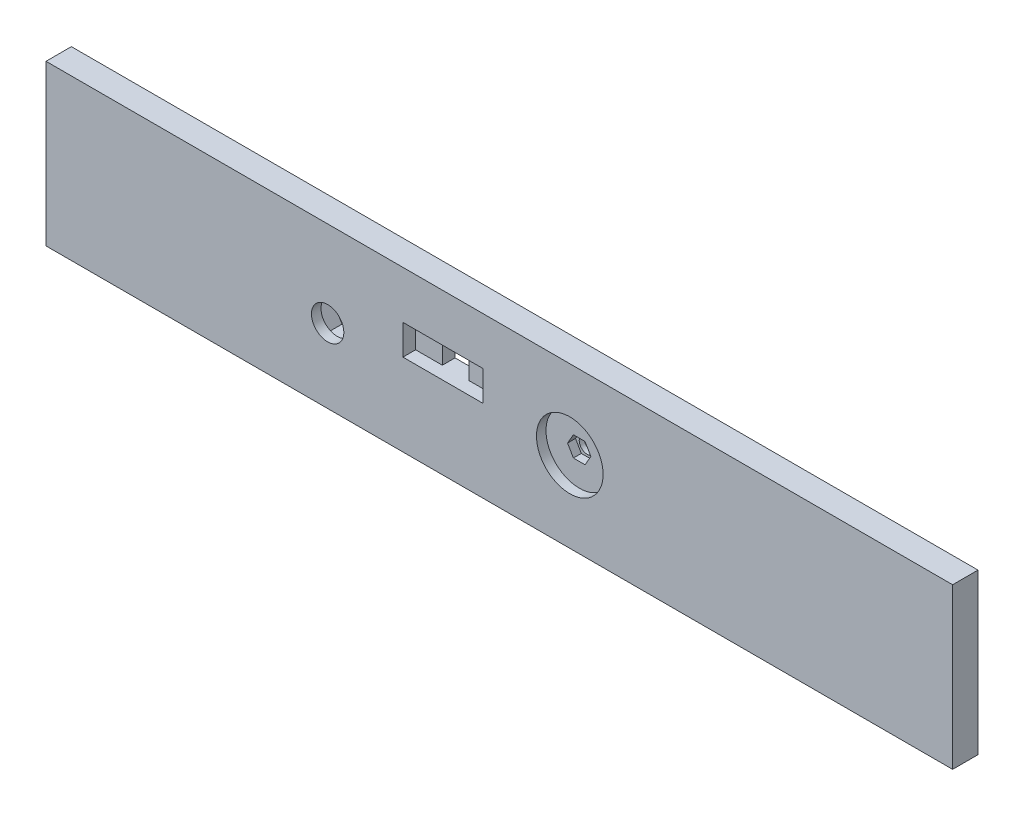
SolidWorks part; units mm, degrees
ref_plane "Front Plane" through (0, 0, 0) normal (0, 0, 1) x (1, 0, 0)
ref_plane "Top Plane" through (0, 0, 0) normal (0, 1, 0) x (1, 0, 0)
ref_plane "Right Plane" through (0, 0, 0) normal (1, 0, 0) x (0, 0, -1)
sketch "Sketch1" plane through (0, 0, 0) normal (0, 0, 1) x (1, 0, 0)
  line L1 (0, 0) -> (571.5, 0)
  line L2 (0, 0) -> (0, 100.8)
  line L3 (0, 100.8) -> (571.5, 100.8)
  line L4 (571.5, 0) -> (571.5, 100.8)
  dimension "D1" = 100.8
  dimension "D2" = 571.5
extrude "Boss-Extrude1" add sketch "Sketch1" along normal mid plane 16
sketch "Sketch4" plane through (0, 0, -8) normal (0, 0, -1) x (-1, 0, 0)
  line L3 (-571.5, 100.8) -> (0, 100.8) construction
  circle A0 centre (-330.1236, 50.8) radius 7.5
  dimension "D3" = 15
  dimension "D1" = 50
extrude "Cut-Extrude3" cut sketch "Sketch4" against normal blind 2
sketch "Sketch5" plane through (0, 0, -6) normal (0, 0, -1) x (-1, 0, 0)
  circle A0 centre (-330.1236, 50.8) radius 5
  dimension "D1" = 10
extrude "Cut-Extrude4" cut sketch "Sketch5" against normal through all
sketch "Sketch6" plane through (0, 0, 8) normal (0, 0, 1) x (1, 0, 0)
  line L1 (337.4675, 50.8) -> (333.7956, 57.16)
  line L2 (333.7956, 57.16) -> (326.4517, 57.16)
  line L3 (326.4517, 57.16) -> (322.7797, 50.8)
  line L4 (322.7797, 50.8) -> (326.4517, 44.44)
  line L5 (326.4517, 44.44) -> (333.7956, 44.44)
  line L6 (333.7956, 44.44) -> (337.4675, 50.8)
  circle A0 centre (330.1236, 50.8) radius 6.36 construction
  dimension "D1" = 12.72
extrude "Cut-Extrude5" cut sketch "Sketch6" against normal blind 11
sketch "Sketch9" plane through (0, 0, 8) normal (0, 0, 1) x (1, 0, 0)
  circle A0 centre (177.5367, 46.6) radius 10.2
  dimension "D1" = 20.4
extrude "power and usb cables" cut sketch "Sketch9" against normal through all
sketch "Sketch10" plane through (0, 0, 8) normal (0, 0, 1) x (1, 0, 0)
  circle A0 centre (330.1639, 50.8218) radius 21
extrude "Cut-Extrude6" cut sketch "Sketch10" against normal blind 6
sketch "Sketch12" plane through (0, 0, -8) normal (0, 0, -1) x (-1, 0, 0)
  line L0 (-164.3354, 47.7347) -> (-169.9534, 57.4654) construction
  line L1 (-163.6803, 46.6) -> (-170.6085, 58.6)
  line L2 (-170.6085, 58.6) -> (-184.4649, 58.6)
  line L3 (-184.4649, 58.6) -> (-191.3931, 46.6)
  line L4 (-191.3931, 46.6) -> (-184.4649, 34.6)
  line L5 (-184.4649, 34.6) -> (-170.6085, 34.6)
  line L6 (-170.6085, 34.6) -> (-163.6803, 46.6)
  circle A0 centre (-177.5367, 46.6) radius 12 construction
  dimension "D1" = 0
extrude "Cut-Extrude8" cut sketch "Sketch12" against normal blind 10
sketch "Sketch13" plane through (0, 0, -8) normal (0, 0, -1) x (-1, 0, 0)
  line L0 (-275.4, 70.8) -> (-225, 70.8) construction
  line L1 (-258.55, 70.8) -> (-241.85, 70.8)
  line L2 (-258.55, 70.8) -> (-258.55, 51.8)
  line L3 (-258.55, 51.8) -> (-241.85, 51.8)
  line L4 (-241.85, 70.8) -> (-241.85, 51.8)
  line L5 (-225, 51.8) -> (-275.4, 51.8) construction
  circle A0 centre (-243.85, 68.92) radius 0.255 construction
  circle A1 centre (-256.55, 68.92) radius 0.255 construction
  dimension "D1" = 2
  dimension "D2" = 2
extrude "Cut-Extrude9" cut sketch "Sketch13" against normal through all and the other way through all
sketch "Sketch14" plane through (0, 0, 8) normal (0, 0, 1) x (1, 0, 0)
  line L1 (225, 70.8) -> (275.4, 70.8)
  line L2 (225, 70.8) -> (225, 51.8)
  line L3 (225, 51.8) -> (275.4, 51.8)
  line L4 (275.4, 70.8) -> (275.4, 51.8)
extrude "Cut-Extrude10" cut sketch "Sketch14" against normal blind 8
sketch "Sketch15" plane through (0, 0, -8) normal (0, 0, -1) x (-1, 0, 0)
  circle A0 centre (-330.1639, 50.8218) radius 15
  dimension "D1" = 30
extrude "Cut-Extrude11" cut sketch "Sketch15" against normal blind 2
